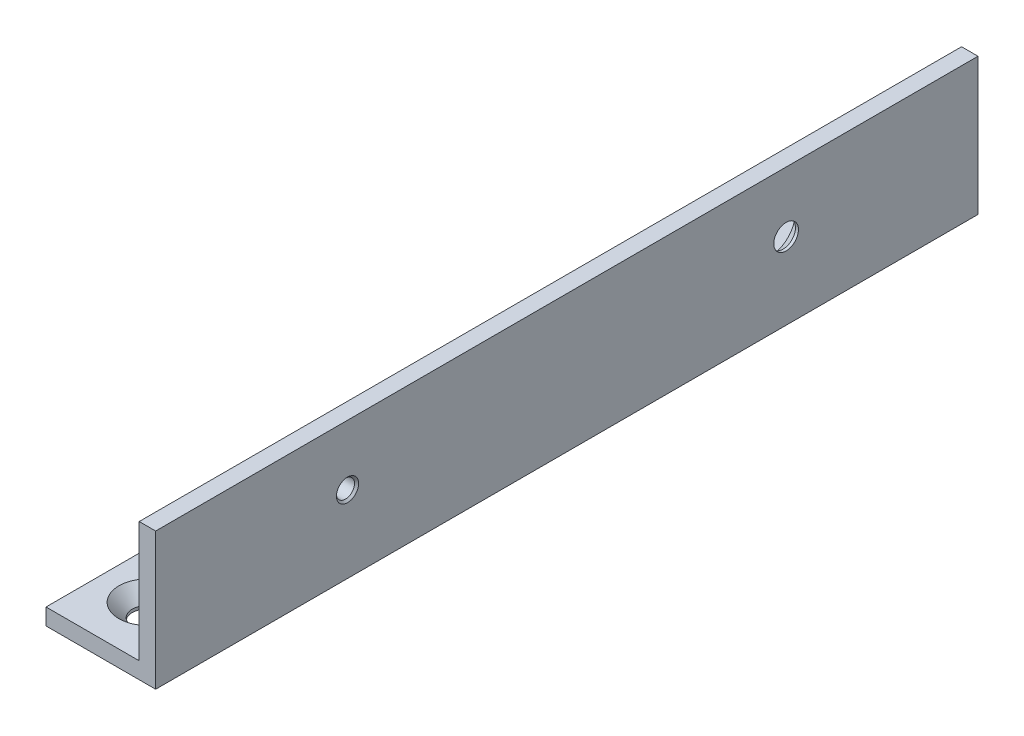
SolidWorks part; units mm, degrees
material "6063-T6"
ref_plane "Plan de face" through (0, 0, 0) normal (0, 0, 1) x (1, 0, 0)
ref_plane "Plan de dessus" through (0, 0, 0) normal (0, 1, 0) x (1, 0, 0)
ref_plane "Plan de droite" through (0, 0, 0) normal (1, 0, 0) x (0, 0, -1)
sketch "Esquisse1" plane through (0, 0, 0) normal (0, 0, 1) x (1, 0, 0)
  line L0 (0, 25) -> (0, 0)
  line L2 (0, 25) -> (-3, 25)
  line L3 (-3, 25) -> (-3, 3)
  line L4 (-20, 3) -> (-20, 0)
  line L5 (-3, 3) -> (0, 0) construction
  line L6 (-3, 3) -> (-20, 3)
  line L7 (-20, 1.5) -> (-1.5, 1.5) construction
  line L8 (-1.5, 1.5) -> (-1.5, 25) construction
  line L9 (0, 0) -> (-20, 0)
  point P2 (0, 0)
  dimension "D1" = 3
  dimension "D2" = 3
  dimension "D3" = 20
  dimension "D4" = 90
  dimension "D5" = 25
  dimension "D6" = 90
extrude "Boss.-Extru.1" add sketch "Esquisse1" along normal blind 150 contours L6 L4 L9 L0 L2 L3
hole_wizard "Fraisage pour vis à tête fraisée M41" positions "Esquisse2" profile "Esquisse3" countersink size "M4" standard "DIN"
sketch "Esquisse2" plane through (-3, 0, 0) normal (-1, 0, 0) x (0, 0, 1)
  line L0 (35, 25) -> (35, 3) construction
  line L1 (150, 25) -> (0, 25) construction
  line L2 (150, 3) -> (0, 3) construction
  line L3 (0, 25) -> (0, 3) construction
  point P9 (35, 14)
  dimension "D1" = 35
sketch "Esquisse3" plane through (-3, 14, 35) normal (0, 1, 0) x (0, 0, 1)
  line L0 (0, 0) -> (0, 26.3519)
  line L1 (0, 26.3519) -> (2.25, 25)
  line L2 (2.25, 25) -> (2.25, 2.45)
  line L3 (2.25, 2.45) -> (4.7, 0)
  line L5 (4.7, 0) -> (0, 0)
  line L6 (-2.25, 2.45) -> (-4.7, 0) construction
  line L10 (0, 26.3519) -> (-2.25, 25) construction
  line L11 (0, -6.35) -> (0, 107.95) construction
  dimension "Diamètre du perçage" = 4.5
  dimension "Profondeur du perçage" = 25
  dimension "Diamètre du fraisage entrant" = 9.4
  dimension "Angle du fraisage entrant" = 90
  dimension "Angle de pointe" = 118
hole_wizard "Trou taraudé M51" positions "Esquisse4" profile "Esquisse6" tap size "M4" standard "DIN" end condition through all
sketch "Esquisse4" plane through (0, 0, 0) normal (1, 0, 0) x (0, 0, -1)
  point P0 (-115, 14)
sketch "Esquisse6" plane through (0, 14, 115) normal (0, 1, 0) x (0, 0, -1)
  line L0 (0, 0) -> (0, 3)
  line L1 (0, 3) -> (2.025, 3)
  line L2 (1.65, 2.625) -> (1.65, 0.375)
  line L3 (1.65, 0.375) -> (2.025, 0)
  line L5 (2.025, 0) -> (0, 0)
  line L6 (-1.65, 0.375) -> (-2.025, 0) construction
  line L7 (2.025, 3) -> (1.65, 2.625)
  line L8 (-2.025, 3) -> (-1.65, 2.625) construction
  line L11 (0, -6.35) -> (0, 107.95) construction
  dimension "Diamètre du trou pour taraudage jusqu'au prochain" = 3.3
  dimension "Profondeur du trou pour taraudage jusqu'au prochain" = 3
  dimension "Diamètre du fraisage entrant" = 4.05
  dimension "Angle du fraisage entrant" = 90
  dimension "Diamètre du fraisage débouchant" = 4.05
  dimension "Angle du fraisage débouchant" = 90
cosmetic thread "Filetage de perçage1"
hole_wizard "Fraisage pour vis à tête fraisée M52" positions "Esquisse7" profile "Esquisse8" countersink size "M5" standard "DIN" end condition through all
sketch "Esquisse7" plane through (0, 3, 0) normal (0, 1, 0) x (1, 0, 0)
  line L0 (-11.5, -150) -> (-11.5, -140) construction
  line L1 (-3, -150) -> (-20, -150) construction
  line L2 (-11.5, -140) -> (-11.5, -75) construction
  line L3 (-11.5, -75) -> (-11.5, -10) construction
  line L4 (-11.5, -10) -> (-11.5, 0) construction
  line L5 (-3, 0) -> (-20, 0) construction
  point P0 (-11.5, -75)
  point P2 (-11.5, -140)
  point P4 (-11.5, -10)
  dimension "D1" = 10
sketch "Esquisse8" plane through (-11.5, 3, 75) normal (1, 0, 0) x (0, 0, 1)
  line L0 (0, 0) -> (0, 3)
  line L1 (0, 3) -> (2.75, 3)
  line L2 (2.75, 3) -> (2.75, 2.45)
  line L3 (2.75, 2.45) -> (5.2, 0)
  line L5 (5.2, 0) -> (0, 0)
  line L6 (-2.75, 2.45) -> (-5.2, 0) construction
  line L11 (0, -6.35) -> (0, 107.95) construction
  dimension "Diamètre du perçage jusqu'au prochain" = 5.5
  dimension "Profondeur du perçage jusqu'au prochain" = 3
  dimension "Diamètre du fraisage entrant" = 10.4
  dimension "Angle du fraisage entrant" = 90
